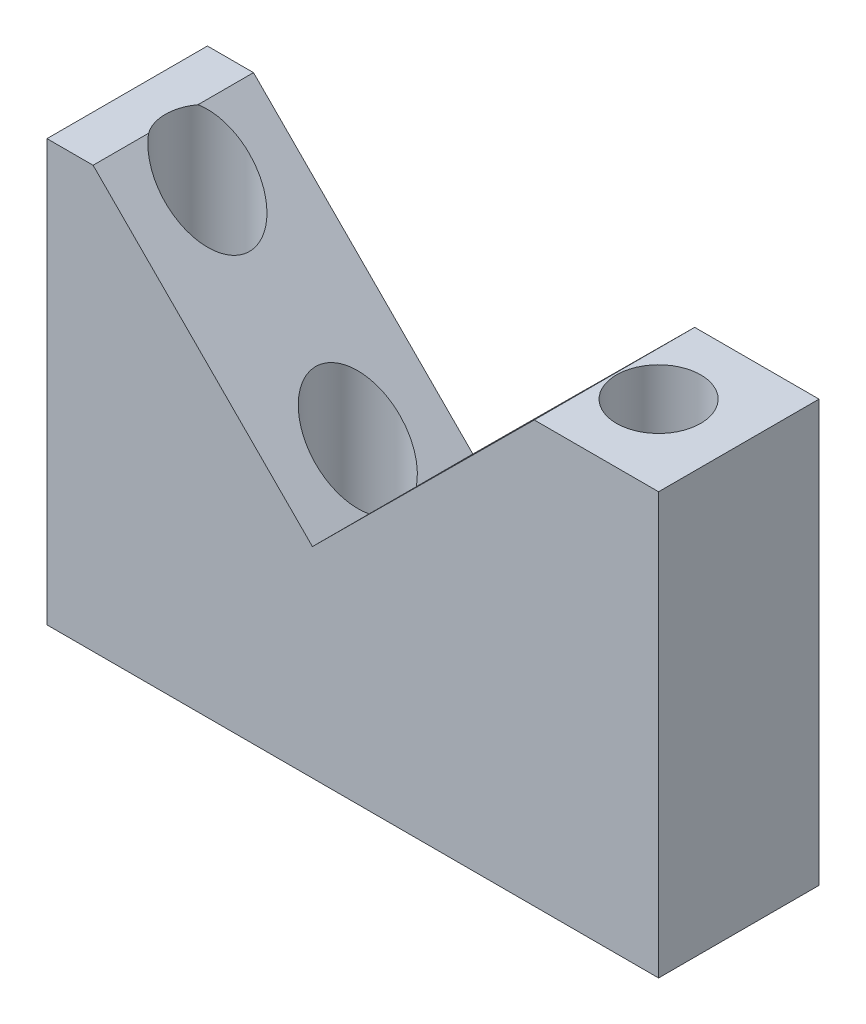
SolidWorks part; units mm, degrees
ref_plane "Front Plane" through (0, 0, 0) normal (0, 0, 1) x (1, 0, 0)
ref_plane "Top Plane" through (0, 0, 0) normal (0, 1, 0) x (1, 0, 0)
ref_plane "Right Plane" through (0, 0, 0) normal (1, 0, 0) x (0, 0, -1)
sketch "Sketch1" plane through (0, 0, 0) normal (0, 1, 0) x (1, 0, 0)
  line L1 (-11.5, 4) -> (19, 4)
  line L2 (-11.5, 4) -> (-11.5, -4)
  line L3 (-11.5, -4) -> (19, -4)
  line L4 (19, 4) -> (19, -4)
  circle A0 centre (0, 0) radius 2.1
  circle A1 centre (-7.5, 0) radius 2.1
  circle A2 centre (7.5, 0) radius 2.1
  circle A3 centre (15, 0) radius 2.1
  dimension "D1" = 4.2
  dimension "D2" = 7.5
  dimension "D3" = 4.2
  dimension "D6" = 4
  dimension "D8" = 4
  dimension "D5" = 4
  dimension "D7" = 4
  dimension "D4" = 2
extrude "Boss-Extrude1" add sketch "Sketch1" along normal blind 21
sketch "Sketch2" plane through (0, 0, 4) normal (0, 0, 1) x (1, 0, 0)
  line L0 (12.8, 21) -> (1.7384, 10)
  line L1 (-11.5, 21) -> (19, 21) construction
  line L2 (-11.5, 0) -> (19, 0) construction
  line L4 (19, 21) -> (19, 0) construction
  line L5 (1.7384, 10) -> (-9.2003, 21)
  line L6 (-9.2003, 21) -> (12.8, 21)
  dimension "D1" = 44.84
  dimension "D2" = 6.2
  dimension "D3" = 10
  dimension "D4" = 45.16
extrude "Cut-Extrude1" cut sketch "Sketch2" against normal blind 17.5
sketch "Sketch4" plane through (19, 0, 0) normal (1, 0, 0) x (0, 0, -1)
  line L0 (-4, 0) -> (4, 0) construction
  line L1 (4, 21) -> (4, 0) construction
  circle A0 centre (0, 4) radius 2.1
  dimension "D1" = 4.2
  dimension "D2" = 4
  dimension "D3" = 4
extrude "Cut-Extrude3" cut sketch "Sketch4" against normal blind 38.5
sketch "Sketch6" plane through (0, 0, 0) normal (0, -1, 0) x (1, 0, 0)
  circle A0 centre (-7.5, 0) radius 2.1
  circle A1 centre (0, 0) radius 2.1
  circle A2 centre (7.5, 0) radius 2.1
  circle A3 centre (15, 0) radius 2.1
extrude "Boss-Extrude3" add sketch "Sketch6" against normal blind 2
sketch "Sketch7" plane through (19, 0, 0) normal (1, 0, 0) x (0, 0, -1)
  circle A0 centre (0, 4) radius 2.1
extrude "Boss-Extrude4" add sketch "Sketch7" against normal blind 3
